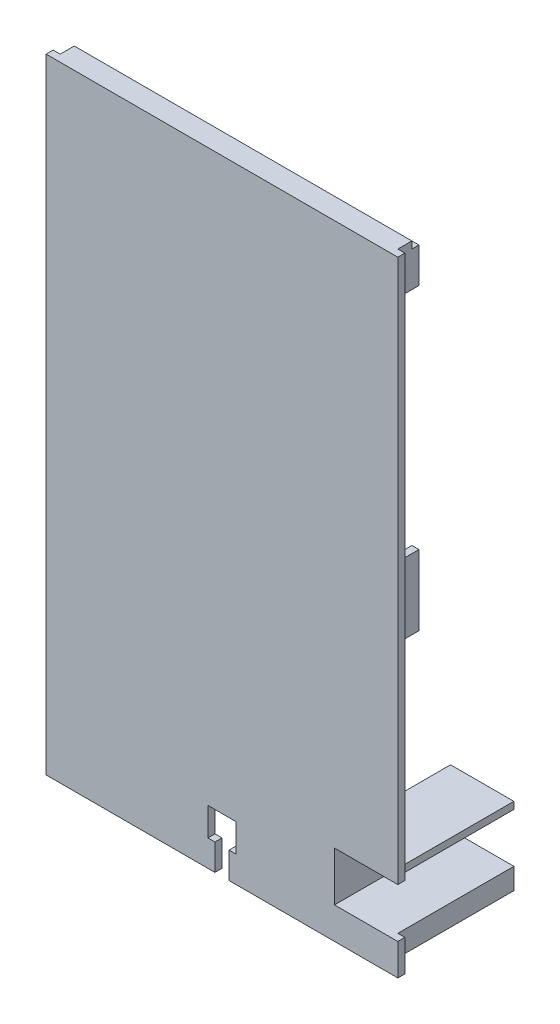
SolidWorks part; units mm, degrees
ref_plane "Front Plane" through (0, 0, 0) normal (0, 0, 1) x (1, 0, 0)
ref_plane "Top Plane" through (0, 0, 0) normal (0, 1, 0) x (1, 0, 0)
ref_plane "Right Plane" through (0, 0, 0) normal (1, 0, 0) x (0, 0, -1)
sketch "Sketch1" plane through (0, 0, 0) normal (0, 0, 1) x (1, 0, 0)
  line L1 (0, 0) -> (100, 0)
  line L2 (0, 0) -> (0, 177.5)
  line L3 (0, 177.5) -> (100, 177.5)
  line L4 (100, 0) -> (100, 177.5)
  dimension "D1" = 177.5
  dimension "D2" = 100
extrude "Boss-Extrude1" add sketch "Sketch1" along normal blind 2
sketch "Sketch2" plane through (0, 0, 0) normal (0, 0, -1) x (-1, 0, 0)
  line L0 (-98, 175.5) -> (-2, 175.5) construction
  line L1 (-2, 175.5) -> (-2, 3) construction
  line L2 (-2, 3) -> (-98, 3) construction
  line L3 (-98, 3) -> (-98, 175.5) construction
  line L4 (-100, 177.5) -> (0, 177.5) construction
  line L5 (0, 177.5) -> (0, 0) construction
  line L6 (-100, 0) -> (-100, 177.5) construction
  line L7 (0, 0) -> (-100, 0) construction
  dimension "D1" = 2
  dimension "D2" = 2
  dimension "D3" = 2
  dimension "D4" = 3
sketch "Sketch3" plane through (0, 0, 0) normal (0, 0, -1) x (-1, 0, 0)
  line L0 (-98, 175.5) -> (-88, 175.5)
  line L1 (-98, 175.5) -> (-2, 175.5) construction
  line L2 (-88, 175.5) -> (-88, 173.5)
  line L3 (-88, 173.5) -> (-96, 173.5)
  line L4 (-96, 173.5) -> (-96, 165.5)
  line L5 (-96, 165.5) -> (-98, 165.5)
  line L6 (-98, 3) -> (-98, 175.5) construction
  line L7 (-98, 165.5) -> (-98, 175.5)
  line L8 (-12, 175.5) -> (-2, 175.5)
  line L9 (-2, 175.5) -> (-2, 165.5)
  line L10 (-2, 175.5) -> (-2, 3) construction
  line L11 (-2, 165.5) -> (-4, 165.5)
  line L12 (-4, 165.5) -> (-4, 173.5)
  line L13 (-4, 173.5) -> (-12, 173.5)
  line L14 (-12, 173.5) -> (-12, 175.5)
  line L15 (-2, 3) -> (-12, 3)
  line L16 (-98, 100.5) -> (-96, 100.5)
  line L17 (-98, 100.5) -> (-98, 80.5)
  line L18 (-98, 80.5) -> (-96, 80.5)
  line L19 (-96, 100.5) -> (-96, 80.5)
  line L20 (-2, 100.5) -> (-4, 100.5)
  line L21 (-2, 100.5) -> (-2, 80.5)
  line L22 (-2, 80.5) -> (-4, 80.5)
  line L23 (-4, 100.5) -> (-4, 80.5)
  line L26 (-2, 3) -> (-98, 3) construction
  line L31 (-12, 3) -> (-12, 5)
  line L32 (-12, 5) -> (-4, 5)
  line L33 (-4, 5) -> (-4, 13)
  line L34 (-4, 13) -> (-2, 13)
  line L35 (-2, 13) -> (-2, 3)
  dimension "D1" = 2
  dimension "D2" = 2
  dimension "D3" = 10
  dimension "D4" = 10
  dimension "D5" = 10
  dimension "D6" = 10
  dimension "D7" = 2
  dimension "D8" = 2
  dimension "D9" = 2
  dimension "D10" = 2
  dimension "D11" = 20
  dimension "D12" = 20
  dimension "D13" = 75
  dimension "D14" = 75
  dimension "D19" = 2
  dimension "D20" = 2
  dimension "D21" = 10
  dimension "D22" = 10
extrude "Boss-Extrude2" add sketch "Sketch3" along normal blind 6
sketch "Sketch4" plane through (0, 0, 0) normal (0, 0, -1) x (-1, 0, 0)
  line L0 (-100, 177.5) -> (0, 177.5) construction
  line L1 (-98, 175.5) -> (-2, 175.5)
  line L2 (-98, 175.5) -> (-98, 177.5)
  line L3 (-98, 177.5) -> (-2, 177.5)
  line L4 (-2, 175.5) -> (-2, 177.5)
extrude "Boss-Extrude3" add sketch "Sketch4" along normal blind 4
sketch "Sketch5" plane through (0, 0, 0) normal (0, 0, -1) x (-1, 0, 0)
  line L0 (-2, 3) -> (-98, 3) construction
  line L20 (-98, 3) -> (-80, 3)
  line L21 (-80, 3) -> (-80, 25)
  line L22 (-80, 25) -> (-98, 25)
  line L23 (-98, 3) -> (-98, 175.5) construction
  line L24 (-98, 25) -> (-98, 23)
  line L25 (-98, 23) -> (-82, 23)
  line L26 (-82, 23) -> (-82, 9)
  line L27 (-82, 9) -> (-98, 9)
  line L28 (-98, 9) -> (-98, 3)
  dimension "D6" = 18
  dimension "D7" = 16
  dimension "D8" = 6
  dimension "D9" = 14
  dimension "D10" = 2
extrude "Boss-Extrude5" add sketch "Sketch5" along normal blind 33
sketch "Sketch7" plane through (0, 0, 0) normal (0, 0, -1) x (-1, 0, 0)
  line L0 (-82, 9) -> (-100, 9)
  line L1 (-100, 0) -> (-100, 177.5) construction
  line L2 (-82, 9) -> (-82, 23)
  line L3 (-82, 23) -> (-100, 23)
  line L4 (-100, 23) -> (-100, 9)
extrude "Cut-Extrude2" cut sketch "Sketch7" against normal through all
sketch "Sketch8" plane through (0, 0, 0) normal (0, 0, -1) x (-1, 0, 0)
  line L0 (-48, 0) -> (-48, 7.5)
  line L1 (0, 0) -> (-100, 0) construction
  line L2 (-48, 7.5) -> (-46, 7.5)
  line L3 (-46, 7.5) -> (-46, 15.5)
  line L4 (-46, 15.5) -> (-54, 15.5)
  line L5 (-54, 15.5) -> (-54, 7.5)
  line L6 (-54, 7.5) -> (-52, 7.5)
  line L7 (-52, 7.5) -> (-52, 0)
  line L8 (-50, 0) -> (-50, 177.5) construction
  line L9 (-2, 177.5) -> (-98, 177.5) construction
  line L10 (-52, 0) -> (-48, 0)
  dimension "D1" = 2
  dimension "D2" = 2
  dimension "D3" = 2
  dimension "D4" = 2
  dimension "D5" = 7.5
  dimension "D6" = 8
  dimension "D7" = 7.5
extrude "Cut-Extrude3" cut sketch "Sketch8" against normal through all
